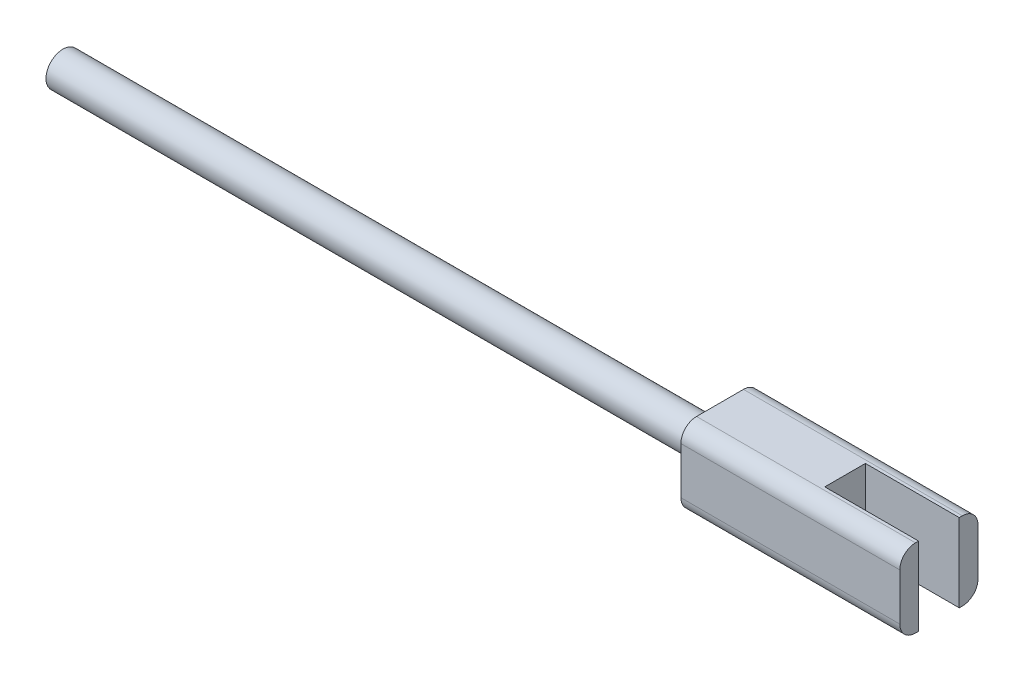
SolidWorks part; units mm, degrees
ref_plane "Front Plane" through (0, 0, 0) normal (0, 0, 1) x (1, 0, 0)
ref_plane "Top Plane" through (0, 0, 0) normal (0, 1, 0) x (1, 0, 0)
ref_plane "Right Plane" through (0, 0, 0) normal (1, 0, 0) x (0, 0, -1)
sketch "Sketch1" plane through (0, 0, 0) normal (1, 0, 0) x (0, 0, -1)
  circle A0 centre (0, 0) radius 1.09
extrude "Boss-Extrude1" add sketch "Sketch1" along normal blind 44.016
ref_plane "Plane1" through (42.016, 0, 0) normal (1, 0, 0) x (0, 0, -1)
sketch "Sketch2" plane through (42.016, 0, 0) normal (1, 0, 0) x (0, 0, -1)
  line L0 (-1.5, -2.5) -> (1.5, -2.5)
  line L1 (2.5, -1.5) -> (2.5, 1.5)
  line L2 (1.5, 2.5) -> (-1.5, 2.5)
  line L3 (-2.5, 1.5) -> (-2.5, -1.5)
  arc A0 (1.5, -2.5) -> (2.5, -1.5) centre (1.5, -1.5) ccw
  arc A1 (2.5, 1.5) -> (1.5, 2.5) centre (1.5, 1.5) ccw
  arc A2 (-1.5, 2.5) -> (-2.5, 1.5) centre (-1.5, 1.5) ccw
  arc A3 (-2.5, -1.5) -> (-1.5, -2.5) centre (-1.5, -1.5) ccw
extrude "Boss-Extrude2" add sketch "Sketch2" along normal blind 14
sketch "Sketch3" plane through (0, 0, 0) normal (0, 1, 0) x (1, 0, 0)
  line L0 (50.016, 1.3) -> (57.016, 1.3)
  line L1 (57.016, 1.3) -> (57.016, -1.3)
  line L2 (57.016, -1.3) -> (50.016, -1.3)
  line L3 (50.016, -1.3) -> (50.016, 1.3)
extrude "Cut-Extrude1" cut sketch "Sketch3" against normal through all and the other way through all
